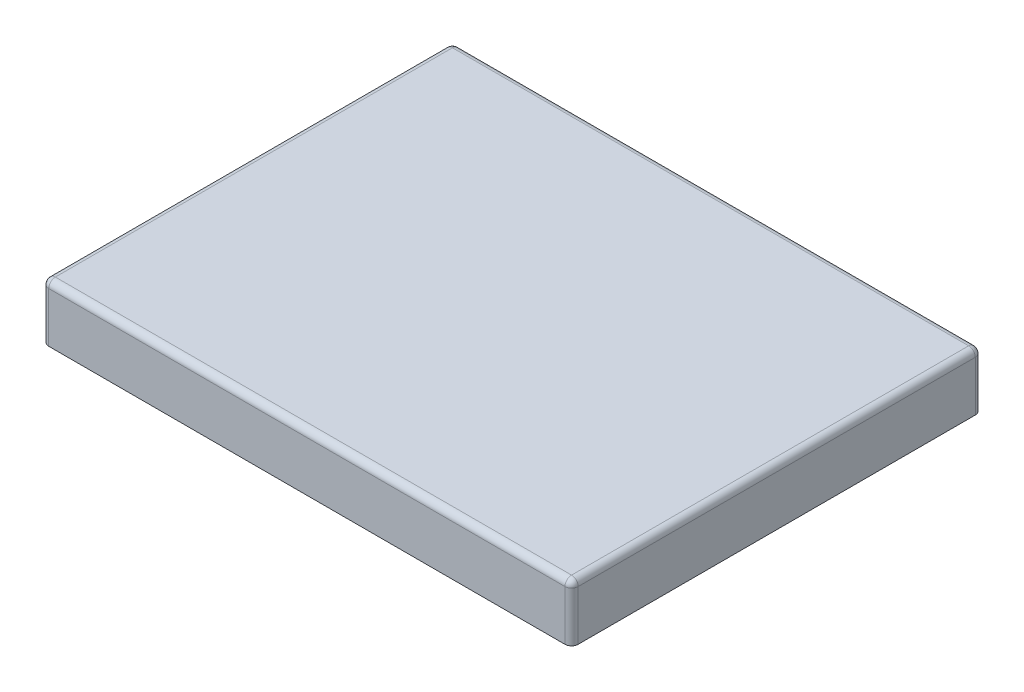
SolidWorks part; units mm, degrees
ref_plane "Front Plane" through (0, 0, 0) normal (0, 0, 1) x (1, 0, 0)
ref_plane "Top Plane" through (0, 0, 0) normal (0, 1, 0) x (1, 0, 0)
ref_plane "Right Plane" through (0, 0, 0) normal (1, 0, 0) x (0, 0, -1)
sketch "Sketch1" plane through (0, 0, 0) normal (0, 1, 0) x (1, 0, 0)
  line L1 (0, 0) -> (508, 0)
  line L2 (0, 0) -> (0, 393.7)
  line L3 (0, 393.7) -> (508, 393.7)
  line L4 (508, 0) -> (508, 393.7)
  line L5 (14.2875, 379.3998) -> (493.7125, 379.3998)
  line L6 (14.2875, 379.3998) -> (14.2875, 14.2748)
  line L7 (14.2875, 14.2748) -> (493.7125, 14.2748)
  line L8 (493.7125, 379.3998) -> (493.7125, 14.2748)
  dimension "D1" = 508
  dimension "D2" = 393.7
  dimension "D3" = 365.125
  dimension "D4" = 14.3002
  dimension "D5" = 479.425
  dimension "D6" = 14.2875
extrude "Boss-Extrude1" add sketch "Sketch1" along normal blind 54.356
sketch "Sketch2" plane through (508, 0, 0) normal (1, 0, 0) x (0, 0, -1)
  line L0 (393.7, 54.356) -> (393.7, 0) construction
  line L1 (0, 54.356) -> (393.7, 54.356)
  line L2 (0, 54.356) -> (0, 41.656)
  line L3 (0, 41.656) -> (393.7, 41.656)
  line L4 (393.7, 54.356) -> (393.7, 41.656)
  dimension "D1" = 12.7
extrude "Boss-Extrude2" add sketch "Sketch2" against normal blind 508
fillet "Fillet1" radius 6.35 8 edges at (508, 27.178, -393.7) (508, 27.178, 0) (0, 27.178, -393.7) (0, 27.178, 0) (508, 54.356, -196.85) (254, 54.356, 0) (0, 54.356, -196.85) (254, 54.356, -393.7)
fillet "Fillet2" radius 6.35 8 edges at (14.2875, 20.828, -379.3998) (14.2875, 41.656, -196.8373) (14.2875, 20.828, -14.2748) (254, 41.656, -14.2748) (493.7125, 20.828, -14.2748) (493.7125, 41.656, -196.8373) (254, 41.656, -379.3998) (493.7125, 20.828, -379.3998)
